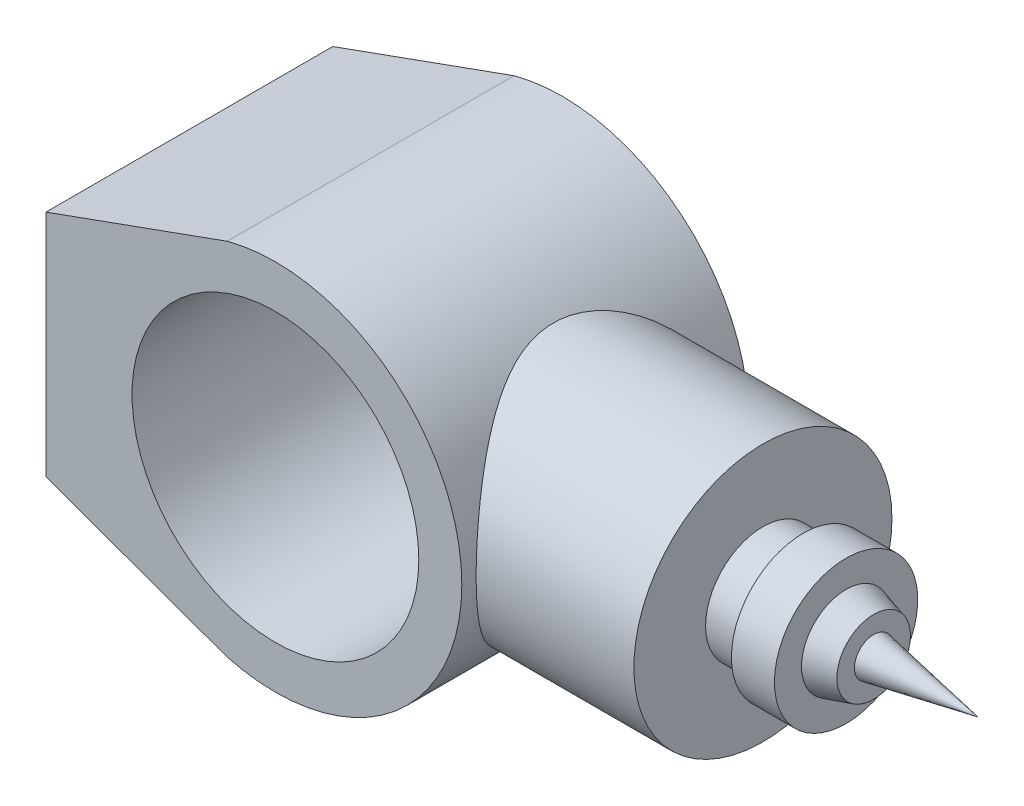
SolidWorks part; units mm, degrees
ref_plane "Front Plane" through (0, 0, 0) normal (0, 0, 1) x (1, 0, 0)
ref_plane "Top Plane" through (0, 0, 0) normal (0, 1, 0) x (1, 0, 0)
ref_plane "Right Plane" through (0, 0, 0) normal (1, 0, 0) x (0, 0, -1)
sketch "Sketch2" plane through (0, 0, 0) normal (0, 0, 1) x (1, 0, 0)
  line L0 (-80, -40) -> (-80, 40)
  line L1 (-80, 40) -> (-16.7748, 62.7981)
  line L2 (-80, -40) -> (-16.7748, -62.7981)
  arc A0 (-16.7748, -62.7981) -> (-16.7748, 62.7981) centre (0, 0) ccw
  circle A1 centre (0, 0) radius 50
  point P1 (0, 0)
  point P4 (0, 0)
  point P7 (-80, 0)
  point P11 (0, 0)
  dimension "D1" = 130
  dimension "D2" = 100
  dimension "D3" = 80
  dimension "D4" = 80
extrude "Boss-Extrude1" add sketch "Sketch2" along normal mid plane 100
ref_plane "Plane1" through (120, 0, 0) normal (1, 0, 0) x (0, 0, -1)
sketch "Sketch3" plane through (120, 0, 0) normal (1, 0, 0) x (0, 0, -1)
  circle A0 centre (0, 0) radius 45
  dimension "D1" = 90
extrude "Boss-Extrude2" add sketch "Sketch3" against normal up to next
sketch "Sketch4" plane through (0, 0, 0) normal (0, 0, 1) x (1, 0, 0)
  line L0 (0, 0) -> (211.8551, 0) construction
  line L1 (120, 0) -> (120, -20)
  line L2 (120, -55) -> (120, 55) construction
  line L3 (120, -20) -> (134, -20)
  line L4 (134, -20) -> (134, -25)
  line L5 (134, -25) -> (149, -25)
  line L6 (149, -25) -> (149, -15.5558)
  line L7 (149, -15.5558) -> (158.6185, -12.8201)
  line L8 (158.6185, -12.8201) -> (158.6185, -6.7371)
  line L9 (158.6185, -6.7371) -> (195, 0)
  line L10 (195, 0) -> (120, 0)
  dimension "D1" = 20
  dimension "D2" = 14
  dimension "D3" = 5
  dimension "D4" = 15
  dimension "D5" = 10
  dimension "D6" = 37
  dimension "D7" = 75
revolve "Revolve1" add sketch "Sketch4" angle 360 about L0
